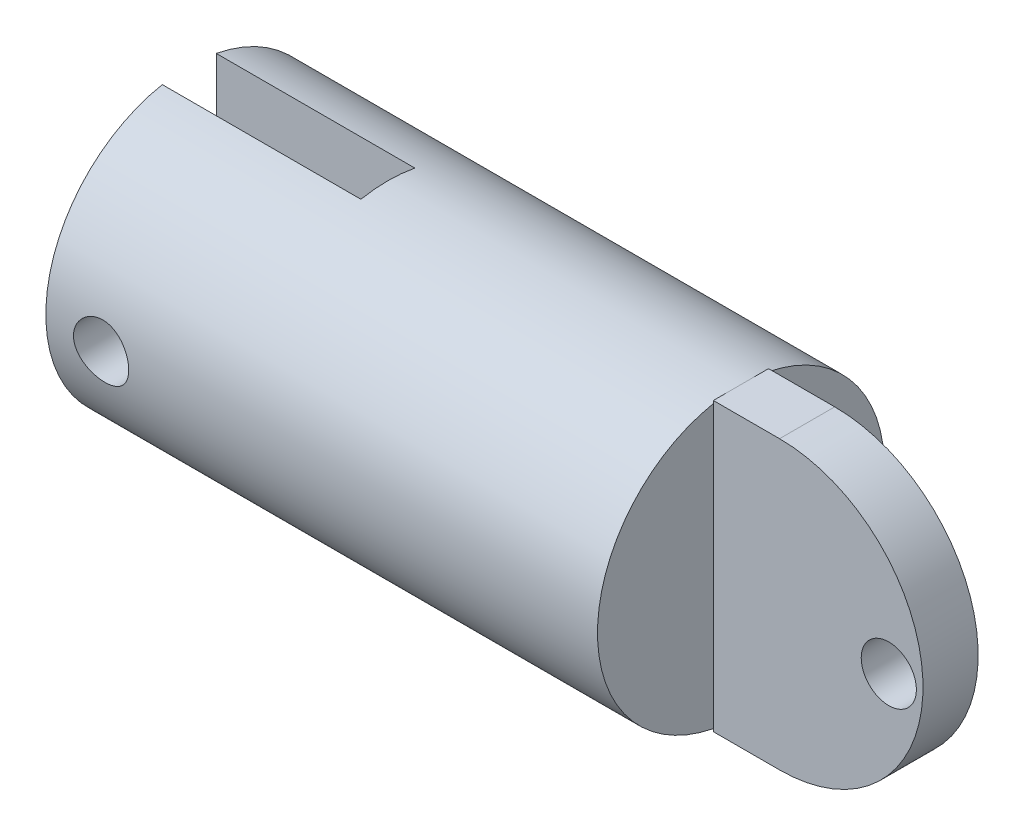
SolidWorks part; units mm, degrees
ref_plane "Front Plane" through (0, 0, 0) normal (0, 0, 1) x (1, 0, 0)
ref_plane "Top Plane" through (0, 0, 0) normal (0, 1, 0) x (1, 0, 0)
ref_plane "Right Plane" through (0, 0, 0) normal (1, 0, 0) x (0, 0, -1)
sketch "Sketch1" plane through (0, 0, 0) normal (1, 0, 0) x (0, 0, -1)
  circle A0 centre (0, 0) radius 13
  dimension "D1" = 26
extrude "Boss-Extrude1" add sketch "Sketch1" against normal blind 50
sketch "Sketch6" plane through (0, 0, 0) normal (1, 0, 0) x (0, 0, -1)
  line L0 (-2.5, 13) -> (-2.5, -13)
  line L1 (-2.5, 13) -> (2.5, 13)
  line L2 (-2.5, -13) -> (2.5, -13)
  line L3 (2.5, 13) -> (2.5, -13)
  line L4 (-2.5, 13) -> (2.5, -13) construction
  line L5 (-2.5, -13) -> (2.5, 13) construction
  point P1 (0, 0)
  dimension "D1" = 5
  dimension "D2" = 26
extrude "Boss-Extrude3" add sketch "Sketch6" along normal blind 6
sketch "Sketch8" plane through (0, 0, 2.5) normal (0, 0, 1) x (1, 0, 0)
  line L0 (6, 13) -> (6, -13) construction
  line L1 (6, 13) -> (6, -13)
  arc A0 (6, -13) -> (6, 13) centre (6, 0) ccw
extrude "Boss-Extrude4" add sketch "Sketch8" against normal blind 5
sketch "Sketch10" plane through (0, 0, 2.5) normal (0, 0, 1) x (1, 0, 0)
  line L0 (0, 12.7574) -> (0, -12.7574) construction
  line L1 (6, -13) -> (0, -13) construction
  circle A0 centre (15.9, -0.5) radius 2.5
  dimension "D1" = 5
  dimension "D2" = 15.9
  dimension "D3" = 12.5
extrude "Cut-Extrude1" cut sketch "Sketch10" against normal through all and the other way through all
sketch "Sketch12" plane through (-50, 0, 0) normal (-1, 0, 0) x (0, 0, 1)
  line L0 (-2.4468, 13) -> (-2.4468, -13)
  line L1 (-2.4468, 13) -> (2.4468, 13)
  line L2 (-2.4468, -13) -> (2.4468, -13)
  line L3 (2.4468, 13) -> (2.4468, -13)
  line L4 (-2.4468, 13) -> (2.4468, -13) construction
  line L5 (-2.4468, -13) -> (2.4468, 13) construction
  point P0 (0, 0)
  point P1 (0, 0)
  dimension "D1" = 26
extrude "Cut-Extrude2" cut sketch "Sketch12" against normal blind 18
sketch "Sketch13" plane through (0, 0, 0) normal (0, 0, 1) x (1, 0, 0)
  line L0 (-50, 12.7677) -> (-50, -12.7677) construction
  line L3 (-32, -13) -> (0, -13) construction
  circle A0 centre (-45, -0.5) radius 2.5
  dimension "D1" = 5
  dimension "D2" = 5
  dimension "D3" = 12.5
extrude "Cut-Extrude3" cut sketch "Sketch13" against normal through all and the other way through all
